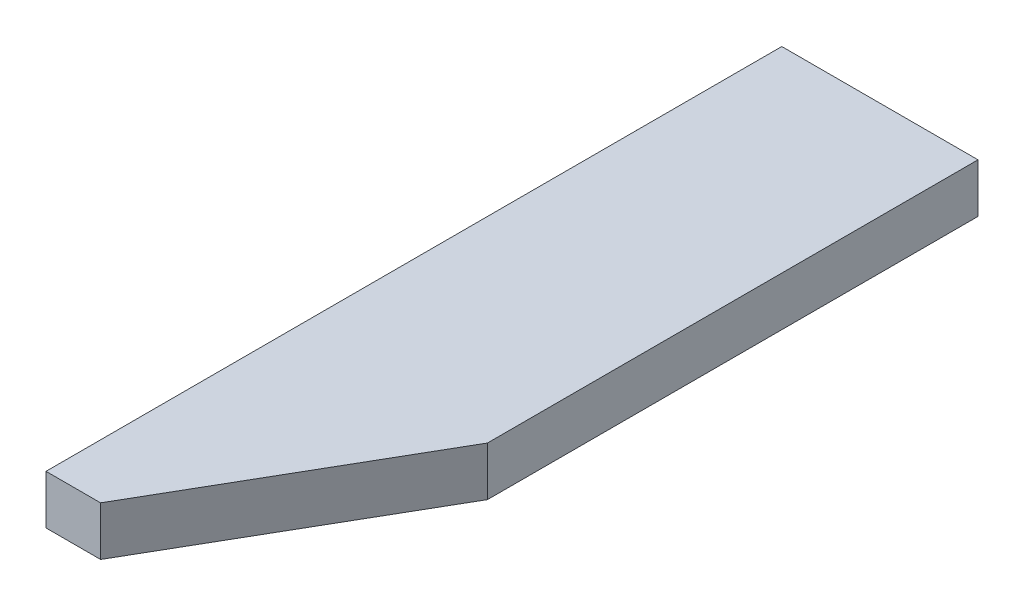
SolidWorks part; units mm, degrees
ref_plane "Přední rovina" through (0, 0, 0) normal (0, 0, 1) x (1, 0, 0)
ref_plane "Horní rovina" through (0, 0, 0) normal (0, 1, 0) x (1, 0, 0)
ref_plane "Pravá rovina" through (0, 0, 0) normal (1, 0, 0) x (0, 0, -1)
sketch "Skica1" plane through (0, 0, 0) normal (0, 0, 1) x (1, 0, 0)
  line L1 (0, 0) -> (40, 0)
  line L2 (0, 0) -> (0, 10)
  line L3 (0, 10) -> (40, 10)
  line L4 (40, 0) -> (40, 10)
  dimension "D1" = 40
  dimension "D2" = 10
extrude "Přidat vysunutím1" add sketch "Skica1" along normal blind 150
sketch "Skica5" plane through (0, 10, 0) normal (0, 1, 0) x (1, 0, 0)
  line L0 (40, -150) -> (40, -100)
  line L1 (40, -150) -> (40, 0) construction
  line L2 (40, -100) -> (11.1325, -150)
  line L3 (40, -150) -> (0, -150) construction
  line L4 (11.1325, -150) -> (40, -150)
  dimension "D1" = 30
  dimension "D2" = 50
extrude "Odebrat vysunutím1" cut sketch "Skica5" against normal through all
